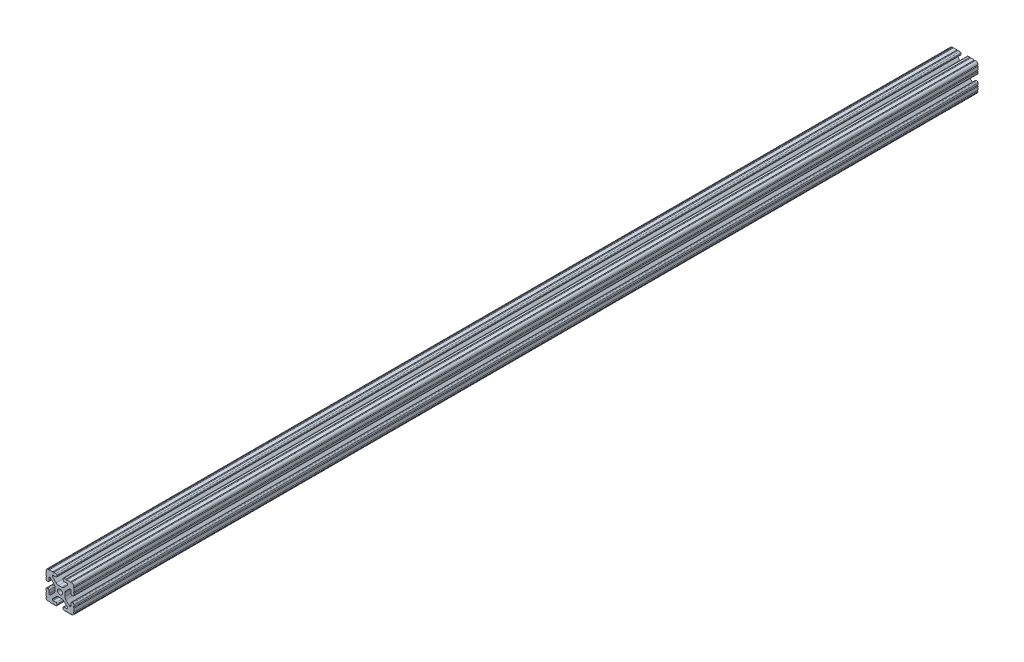
SolidWorks part; units mm, degrees
material "6061 Alloy"
ref_plane "Front Plane" through (0, 0, 0) normal (0, 0, 1) x (1, 0, 0)
ref_plane "Top Plane" through (0, 0, 0) normal (0, 1, 0) x (1, 0, 0)
ref_plane "Right Plane" through (0, 0, 0) normal (1, 0, 0) x (0, 0, -1)
sketch "Sketch1" plane through (0, 0, 0) normal (0, 0, 1) x (1, 0, 0)
  line L0 (0, 25.6181) -> (0, -24.623) construction
  line L1 (-20.8943, 0) -> (20.4607, 0) construction
  line L2 (-10.0229, 12.9148) -> (-5.2522, 8.144)
  line L3 (-10.287, 14.0843) -> (-10.287, 13.5524)
  line L4 (-5.6176, 14.986) -> (-9.3853, 14.986)
  line L5 (-4.064, 17.4964) -> (-4.064, 16.5396)
  line L6 (-7.9742, 19.05) -> (-5.6176, 19.05)
  line L7 (-14.3277, 19.05) -> (-9.4982, 19.05)
  line L8 (-19.05, 9.4961) -> (-19.05, 14.3277)
  line L9 (-19.05, 5.6176) -> (-19.05, 7.9763)
  line L10 (-16.5396, 4.064) -> (-17.4964, 4.064)
  line L11 (-14.986, 9.3853) -> (-14.986, 5.6176)
  line L12 (-13.516, 10.287) -> (-14.0843, 10.287)
  line L13 (-8.1476, 5.2921) -> (-12.8784, 10.0229)
  line L14 (-6.7564, -1.9335) -> (-6.7564, 1.9335)
  line L15 (-12.8784, -10.0229) -> (-8.1476, -5.2921)
  line L16 (-14.0843, -10.287) -> (-13.516, -10.287)
  line L17 (-14.986, -5.6176) -> (-14.986, -9.3853)
  line L18 (-17.4964, -4.064) -> (-16.5396, -4.064)
  line L19 (-19.05, -7.9763) -> (-19.05, -5.6176)
  line L20 (-19.05, -14.3277) -> (-19.05, -9.4961)
  line L21 (-9.4961, -19.05) -> (-14.3277, -19.05)
  line L22 (-5.6176, -19.05) -> (-7.9763, -19.05)
  line L23 (-4.064, -17.4964) -> (-4.064, -16.5396)
  line L24 (10.0229, -12.9148) -> (5.2522, -8.144)
  line L25 (10.287, -14.0843) -> (10.287, -13.5524)
  line L26 (5.6176, -14.986) -> (9.3853, -14.986)
  line L28 (-1.9022, 6.7564) -> (1.9022, 6.7564)
  line L29 (-1.9022, -6.7564) -> (1.9022, -6.7564)
  line L31 (-5.6176, -14.986) -> (-9.3853, -14.986)
  line L32 (-10.287, -14.0843) -> (-10.287, -13.5524)
  line L33 (-10.0229, -12.9148) -> (-5.2522, -8.144)
  line L66 (4.064, -16.5396) -> (4.064, -17.4964)
  line L67 (5.6176, -19.05) -> (7.9763, -19.05)
  line L68 (9.4961, -19.05) -> (14.3277, -19.05)
  line L69 (19.05, -14.3277) -> (19.05, -9.4961)
  line L70 (19.05, -7.9763) -> (19.05, -5.6176)
  line L71 (17.4964, -4.064) -> (16.5396, -4.064)
  line L72 (14.986, -5.6176) -> (14.986, -9.3853)
  line L73 (14.0843, -10.287) -> (13.516, -10.287)
  line L74 (12.8784, -10.0229) -> (8.1476, -5.2921)
  line L75 (6.7564, -1.9335) -> (6.7564, 1.9335)
  line L76 (8.1476, 5.2921) -> (12.8784, 10.0229)
  line L77 (13.516, 10.287) -> (14.0843, 10.287)
  line L78 (14.986, 9.3853) -> (14.986, 5.6176)
  line L79 (16.5396, 4.064) -> (17.4964, 4.064)
  line L80 (19.05, 5.6176) -> (19.05, 7.9763)
  line L81 (19.05, 9.4961) -> (19.05, 14.3277)
  line L82 (14.3277, 19.05) -> (9.4982, 19.05)
  line L83 (7.9742, 19.05) -> (5.6176, 19.05)
  line L84 (4.064, 17.4964) -> (4.064, 16.5396)
  line L85 (5.6176, 14.986) -> (9.3853, 14.986)
  line L86 (10.287, 14.0843) -> (10.287, 13.5524)
  line L87 (10.0229, 12.9148) -> (5.2522, 8.144)
  arc A0 (-10.0229, 12.9148) -> (-10.287, 13.5524) centre (-9.3853, 13.5524) cw
  circle A1 centre (0, 0) radius 3.3274
  arc A2 (-10.287, 14.0843) -> (-9.3853, 14.986) centre (-9.3853, 14.0843) cw
  arc A3 (-4.064, 16.5396) -> (-5.6176, 14.986) centre (-5.6176, 16.5396) cw
  arc A4 (-5.6176, 19.05) -> (-4.064, 17.4964) centre (-5.6176, 17.4964) cw
  arc A5 (-7.9742, 19.05) -> (-9.4982, 19.05) centre (-8.7362, 19.05) cw
  arc A6 (-14.3277, 19.05) -> (-15.8475, 19.05) centre (-15.0876, 18.9933) cw
  arc A7 (-19.05, 15.8475) -> (-15.8475, 19.05) centre (-15.8751, 15.8751) cw
  arc A8 (-19.05, 15.8475) -> (-19.05, 14.3277) centre (-18.9933, 15.0876) cw
  arc A9 (-19.05, 9.4961) -> (-19.05, 7.9763) centre (-18.9933, 8.7362) cw
  arc A10 (-17.4964, 4.064) -> (-19.05, 5.6176) centre (-17.4964, 5.6176) cw
  arc A11 (-14.986, 5.6176) -> (-16.5396, 4.064) centre (-16.5396, 5.6176) cw
  arc A12 (-14.986, 9.3853) -> (-14.0843, 10.287) centre (-14.0843, 9.3853) cw
  arc A13 (-13.516, 10.287) -> (-12.8784, 10.0229) centre (-13.516, 9.3853) cw
  arc A14 (-8.1476, 5.2921) -> (-6.7564, 1.9335) centre (-11.5062, 1.9335) cw
  arc A15 (-6.7564, -1.9335) -> (-8.1476, -5.2921) centre (-11.5062, -1.9335) cw
  arc A16 (-12.8784, -10.0229) -> (-13.516, -10.287) centre (-13.516, -9.3853) cw
  arc A17 (-14.0843, -10.287) -> (-14.986, -9.3853) centre (-14.0843, -9.3853) cw
  arc A18 (-16.5396, -4.064) -> (-14.986, -5.6176) centre (-16.5396, -5.6176) cw
  arc A19 (-19.05, -5.6176) -> (-17.4964, -4.064) centre (-17.4964, -5.6176) cw
  arc A20 (-19.05, -7.9763) -> (-19.05, -9.4961) centre (-18.9933, -8.7362) cw
  arc A21 (-19.05, -14.3277) -> (-19.05, -15.8475) centre (-18.9933, -15.0876) cw
  arc A22 (-15.8475, -19.05) -> (-19.05, -15.8475) centre (-15.8751, -15.8751) cw
  arc A23 (-15.8475, -19.05) -> (-14.3277, -19.05) centre (-15.0876, -18.9933) cw
  arc A24 (-9.4961, -19.05) -> (-7.9763, -19.05) centre (-8.7362, -18.9933) cw
  arc A25 (-4.064, -17.4964) -> (-5.6176, -19.05) centre (-5.6176, -17.4964) cw
  arc A26 (-5.2522, -8.144) -> (-1.9022, -6.7564) centre (-1.9022, -11.494) cw
  arc A27 (1.9022, -6.7564) -> (5.2522, -8.144) centre (1.9022, -11.494) cw
  arc A28 (10.0229, -12.9148) -> (10.287, -13.5524) centre (9.3853, -13.5524) cw
  arc A29 (10.287, -14.0843) -> (9.3853, -14.986) centre (9.3853, -14.0843) cw
  arc A30 (4.064, -16.5396) -> (5.6176, -14.986) centre (5.6176, -16.5396) cw
  arc A31 (-4.064, -16.5396) -> (-5.6176, -14.986) centre (-5.6176, -16.5396) ccw
  arc A32 (-10.287, -14.0843) -> (-9.3853, -14.986) centre (-9.3853, -14.0843) ccw
  arc A33 (-10.0229, -12.9148) -> (-10.287, -13.5524) centre (-9.3853, -13.5524) ccw
  arc A79 (4.064, -17.4964) -> (5.6176, -19.05) centre (5.6176, -17.4964) ccw
  arc A80 (9.4961, -19.05) -> (7.9763, -19.05) centre (8.7362, -18.9933) ccw
  arc A81 (15.8475, -19.05) -> (14.3277, -19.05) centre (15.0876, -18.9933) ccw
  arc A82 (15.8475, -19.05) -> (19.05, -15.8475) centre (15.8751, -15.8751) ccw
  arc A83 (19.05, -14.3277) -> (19.05, -15.8475) centre (18.9933, -15.0876) ccw
  arc A84 (19.05, -7.9763) -> (19.05, -9.4961) centre (18.9933, -8.7362) ccw
  arc A85 (19.05, -5.6176) -> (17.4964, -4.064) centre (17.4964, -5.6176) ccw
  arc A86 (16.5396, -4.064) -> (14.986, -5.6176) centre (16.5396, -5.6176) ccw
  arc A87 (14.0843, -10.287) -> (14.986, -9.3853) centre (14.0843, -9.3853) ccw
  arc A88 (12.8784, -10.0229) -> (13.516, -10.287) centre (13.516, -9.3853) ccw
  arc A89 (6.7564, -1.9335) -> (8.1476, -5.2921) centre (11.5062, -1.9335) ccw
  arc A90 (8.1476, 5.2921) -> (6.7564, 1.9335) centre (11.5062, 1.9335) ccw
  arc A91 (13.516, 10.287) -> (12.8784, 10.0229) centre (13.516, 9.3853) ccw
  arc A92 (14.986, 9.3853) -> (14.0843, 10.287) centre (14.0843, 9.3853) ccw
  arc A93 (14.986, 5.6176) -> (16.5396, 4.064) centre (16.5396, 5.6176) ccw
  arc A94 (17.4964, 4.064) -> (19.05, 5.6176) centre (17.4964, 5.6176) ccw
  arc A95 (19.05, 9.4961) -> (19.05, 7.9763) centre (18.9933, 8.7362) ccw
  arc A96 (19.05, 15.8475) -> (19.05, 14.3277) centre (18.9933, 15.0876) ccw
  arc A97 (19.05, 15.8475) -> (15.8475, 19.05) centre (15.8751, 15.8751) ccw
  arc A98 (14.3277, 19.05) -> (15.8475, 19.05) centre (15.0876, 18.9933) ccw
  arc A99 (7.9742, 19.05) -> (9.4982, 19.05) centre (8.7362, 19.05) ccw
  arc A100 (5.6176, 19.05) -> (4.064, 17.4964) centre (5.6176, 17.4964) ccw
  arc A101 (4.064, 16.5396) -> (5.6176, 14.986) centre (5.6176, 16.5396) ccw
  arc A102 (10.287, 14.0843) -> (9.3853, 14.986) centre (9.3853, 14.0843) ccw
  arc A103 (10.0229, 12.9148) -> (10.287, 13.5524) centre (9.3853, 13.5524) ccw
  arc A104 (1.9022, 6.7564) -> (5.2522, 8.144) centre (1.9022, 11.494) ccw
  arc A105 (-5.2522, 8.144) -> (-1.9022, 6.7564) centre (-1.9022, 11.494) ccw
  dimension "D1" = 6.6548
  dimension "D2" = 19.05
  dimension "D3" = 38.1
  dimension "D4" = 20.574
  dimension "D5" = 13.5128
  dimension "D6" = 4.064
  dimension "D7" = 8.128
  dimension "D8" = 4.064
  dimension "D9" = 12.2936
extrude "Extrude1" add sketch "Sketch1" against normal blind 1231.9
